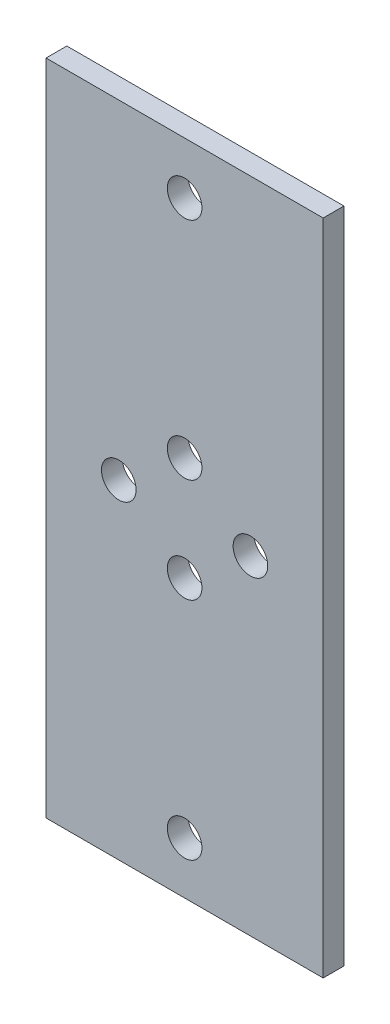
SolidWorks part; units mm, degrees
material "Alloy Steel"
ref_plane "Plano frontal" through (0, 0, 0) normal (0, 0, 1) x (1, 0, 0)
ref_plane "Plano superior" through (0, 0, 0) normal (0, 1, 0) x (1, 0, 0)
ref_plane "Plano direito" through (0, 0, 0) normal (1, 0, 0) x (0, 0, -1)
sketch "Esboço1" plane through (0, 0, 0) normal (0, 0, 1) x (1, 0, 0)
  line L1 (0, 0) -> (40, 0)
  line L2 (0, 0) -> (0, 95)
  line L3 (0, 95) -> (40, 95)
  line L4 (40, 0) -> (40, 95)
  dimension "D1" = 40
  dimension "D2" = 95
extrude "Ressalto-extrusão1" add sketch "Esboço1" along normal blind 3
sketch "Esboço2" plane through (0, 0, 3) normal (0, 0, 1) x (1, 0, 0)
  line L0 (0, 47.5) -> (40, 47.5) construction
  line L1 (0, 95) -> (0, 0) construction
  line L2 (40, 0) -> (40, 95) construction
  line L3 (20, 95) -> (20, 0) construction
  line L4 (40, 95) -> (0, 95) construction
  line L5 (0, 0) -> (40, 0) construction
  circle A1 centre (20, 87.5) radius 2.5
  circle A5 centre (20, 7.5) radius 2.5
  circle A6 centre (10.5, 47.5) radius 2.5
  circle A8 centre (29.5, 47.5) radius 2.5
  circle A9 centre (20, 55) radius 2.5
  circle A10 centre (20, 40) radius 2.5
  dimension "D1" = 5
  dimension "D2" = 7.5
  dimension "D3" = 5
  dimension "D5" = 5
  dimension "D7" = 15
  dimension "D4" = 5
  dimension "D6" = 5
  dimension "D8" = 7.5
  dimension "D10" = 9.5
  dimension "D9" = 19
extrude "Cut-Extrude1" cut sketch "Esboço2" against normal up to next
